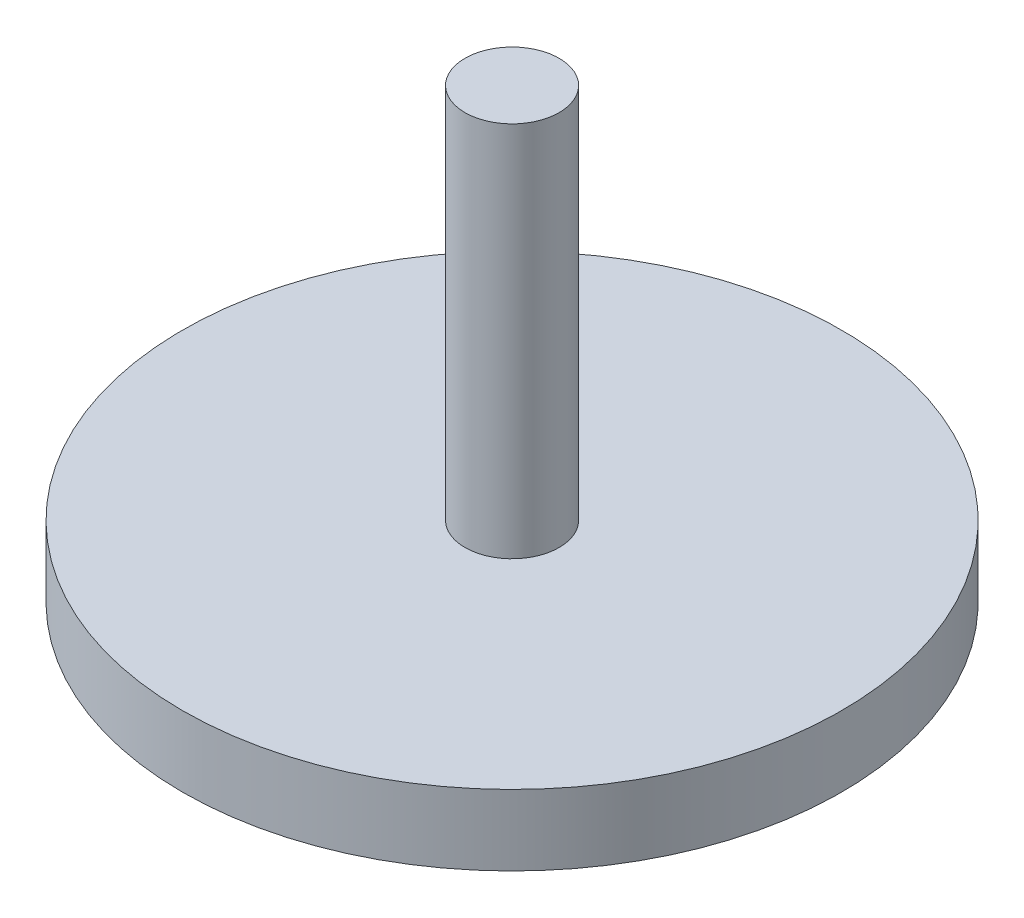
SolidWorks part; units mm, degrees
ref_plane "前视基准面" through (0, 0, 0) normal (0, 0, 1) x (1, 0, 0)
ref_plane "上视基准面" through (0, 0, 0) normal (0, 1, 0) x (1, 0, 0)
ref_plane "右视基准面" through (0, 0, 0) normal (1, 0, 0) x (0, 0, -1)
other "Configuration Table"
sketch "草图1" plane through (0, 0, 0) normal (0, 1, 0) x (1, 0, 0)
  circle A0 centre (0, 0) radius 7
  dimension "D1" = 14
extrude "凸台-拉伸1" add sketch "草图1" along normal blind 1.5 contours A0
sketch "草图2" plane through (0, 1.5, 0) normal (0, 1, 0) x (1, 0, 0)
  circle A0 centre (0, 0) radius 1
  dimension "D1" = 2
extrude "凸台-拉伸2" add sketch "草图2" along normal blind 8
